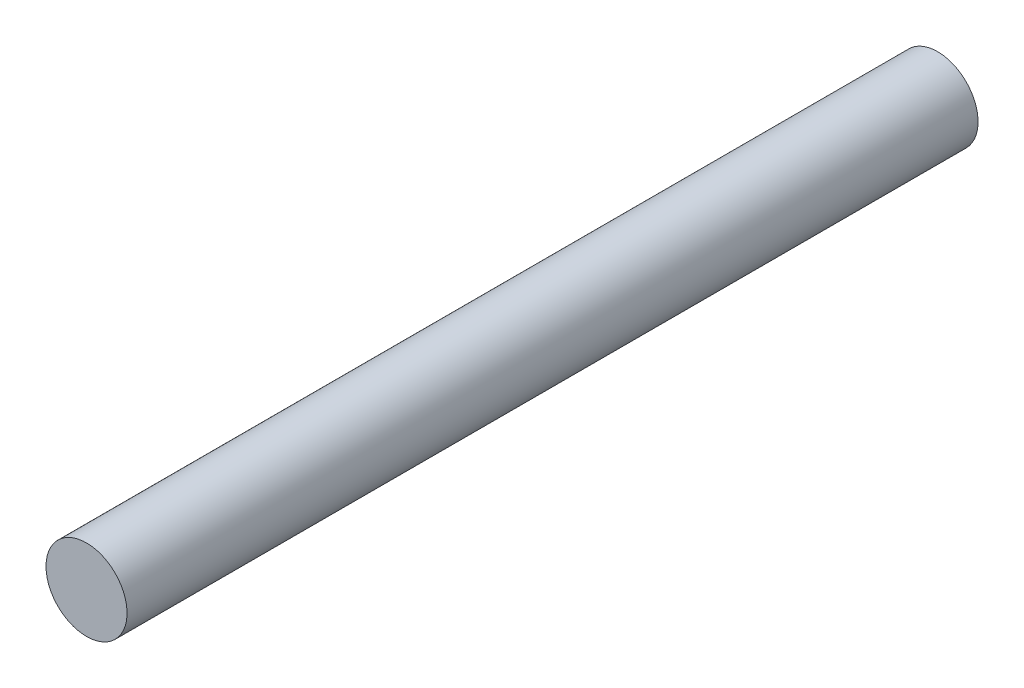
SolidWorks part; units mm, degrees
ref_plane "Plan de face" through (0, 0, 0) normal (0, 0, 1) x (1, 0, 0)
ref_plane "Plan de dessus" through (0, 0, 0) normal (0, 1, 0) x (1, 0, 0)
ref_plane "Plan de droite" through (0, 0, 0) normal (1, 0, 0) x (0, 0, -1)
sketch "Esquisse1" plane through (0, 0, 0) normal (0, 0, 1) x (1, 0, 0)
  circle A0 centre (0, 0) radius 5
  dimension "D1" = 10
extrude "Boss.-Extru.1" add sketch "Esquisse1" along normal up to surface (105 mm away)
